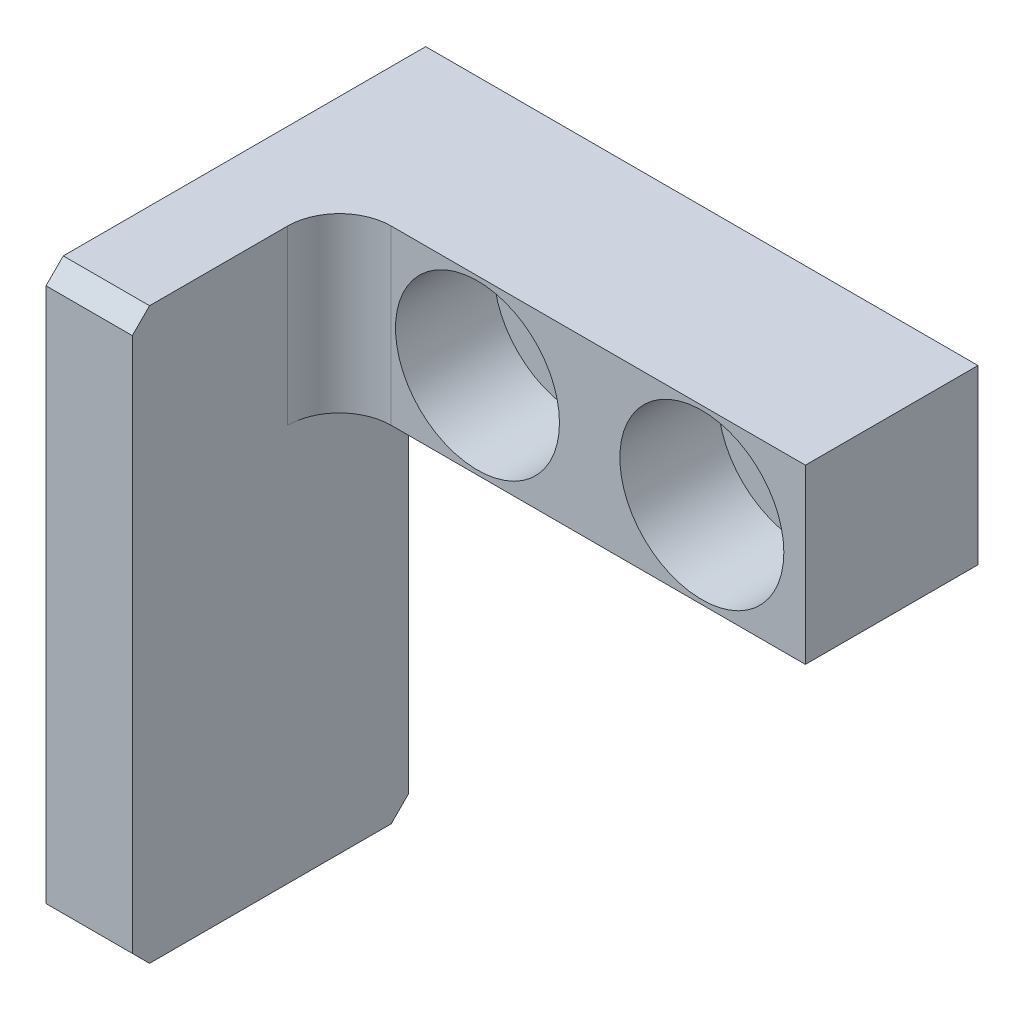
SolidWorks part; units mm, degrees
material "45#"
ref_plane "前视" through (0, 0, 0) normal (0, 0, 1) x (1, 0, 0)
ref_plane "上视" through (0, 0, 0) normal (0, 1, 0) x (1, 0, 0)
ref_plane "右视" through (0, 0, 0) normal (1, 0, 0) x (0, 0, -1)
sketch "草图1" plane through (0, 0, 0) normal (0, 1, 0) x (1, 0, 0)
  line L1 (-16, -11) -> (16, -11)
  line L2 (-16, -11) -> (-16, 11)
  line L3 (-16, 11) -> (16, 11)
  line L4 (16, -11) -> (16, 11)
  line L5 (-16, -11) -> (16, 11) construction
  line L6 (-16, 11) -> (16, -11) construction
  point P0 (0, 0)
  dimension "D1" = 32
  dimension "D2" = 22
extrude "凸台-拉伸1" add sketch "草图1" along normal blind 33
sketch "草图2" plane through (0, 33, 0) normal (0, 1, 0) x (1, 0, 0)
  line L0 (-16, 11) -> (-16, -11) construction
  line L1 (16, -11) -> (-11, -11)
  line L2 (16, -11) -> (16, 1)
  line L3 (16, 1) -> (-11, 1)
  line L4 (-11, -11) -> (-11, 1)
  line L5 (16, 11) -> (-16, 11) construction
  dimension "D1" = 5
  dimension "D2" = 10
extrude "切除-拉伸1" cut sketch "草图2" against normal through all
sketch "草图4" plane through (16, 0, -21) normal (-1, 0, 0) x (0, 0, 1)
  line L1 (20, 0) -> (10, 0)
  line L2 (20, 0) -> (20, 23)
  line L3 (20, 23) -> (10, 23)
  line L4 (10, 0) -> (10, 23)
  line L6 (10, 33) -> (10, 0) construction
  line L7 (20, 33) -> (10, 33) construction
  dimension "D1" = 10
extrude "切除-拉伸2" cut sketch "草图4" along normal up to surface (27 mm away) up to face at (-11, 16.5, 5)
hole_wizard "打孔尺寸根据内六角圆柱头螺钉的类型1" positions "草图6" profile "草图5" counterbore size "M5" standard "Gb" end condition through all
sketch "草图6" plane through (0, 0, -1) normal (0, 0, 1) x (1, 0, 0)
  line L0 (16, 28) -> (14.8759, 28) construction
  line L1 (16, 23) -> (16, 33) construction
  line L3 (-11, 23) -> (-11, 33) construction
  point P0 (-3, 28)
  point P2 (10, 28)
  dimension "D1" = 8
  dimension "D2" = 13
sketch "草图5" plane through (-3, 28, -1) normal (1, 0, 0) x (0, -1, 0)
  line L0 (0, 0) -> (0, 10)
  line L1 (0, 10) -> (2.75, 10)
  line L3 (2.75, 10) -> (2.75, 5.7)
  line L4 (2.75, 5.7) -> (4.75, 5.7)
  line L5 (4.75, 5.7) -> (4.75, 0)
  line L7 (4.75, 0) -> (0, 0)
  line L11 (0, -6.35) -> (0, 107.95) construction
  dimension "通孔孔直径" = 5.5
  dimension "通孔孔深度" = 10
  dimension "柱形沉头孔直径" = 9.5
  dimension "柱形沉头孔深度" = 5.7
sketch "草图8" plane through (-11, 0, 0) normal (1, 0, 0) x (0, 0, -1)
  line L0 (1, 23) -> (11, 23) construction
  line L1 (11, 0) -> (5, 0)
  line L2 (11, 0) -> (11, 23)
  line L3 (11, 23) -> (5, 23)
  line L4 (5, 0) -> (5, 23)
  dimension "D1" = 6
extrude "切除-拉伸3" cut sketch "草图8" against normal through all
hole_wizard "M6 螺纹孔1" [suppressed] positions "草图10" profile "草图9" tap size "M6" standard "Gb"
sketch "草图10" plane through (-16, 0, 0) normal (-1, 0, 0) x (0, 0, 1)
  line L0 (-11, 33) -> (-11, 23) construction
  line L1 (-11, 33) -> (11, 33) construction
  point P0 (2.5, 5.9)
  dimension "D1" = 13.5
  dimension "D2" = 27.1
sketch "草图9" plane through (-16, 5.9, 2.5) normal (0, 1, 0) x (0, 0, 1)
  line L0 (0, 0) -> (0, 32)
  line L1 (0, 32) -> (2.5, 32)
  line L2 (2.5, 32) -> (2.5, 0)
  line L5 (2.5, 0) -> (0, 0)
  line L11 (0, -6.35) -> (0, 107.95) construction
  dimension "通孔螺纹孔钻头直径" = 5
  dimension "通孔螺纹孔钻头深度" = 32
cosmetic thread "孔螺蚊线1" [suppressed] parameters "D2"=6
fillet "圆角1" radius 3 1 edges at (-11, 28, -1)
chamfer "倒角1" distance 1 angle 45 3 edges at (-13.5, 33, 11) (-13.5, 0, -5) (-13.5, 0, 11)
